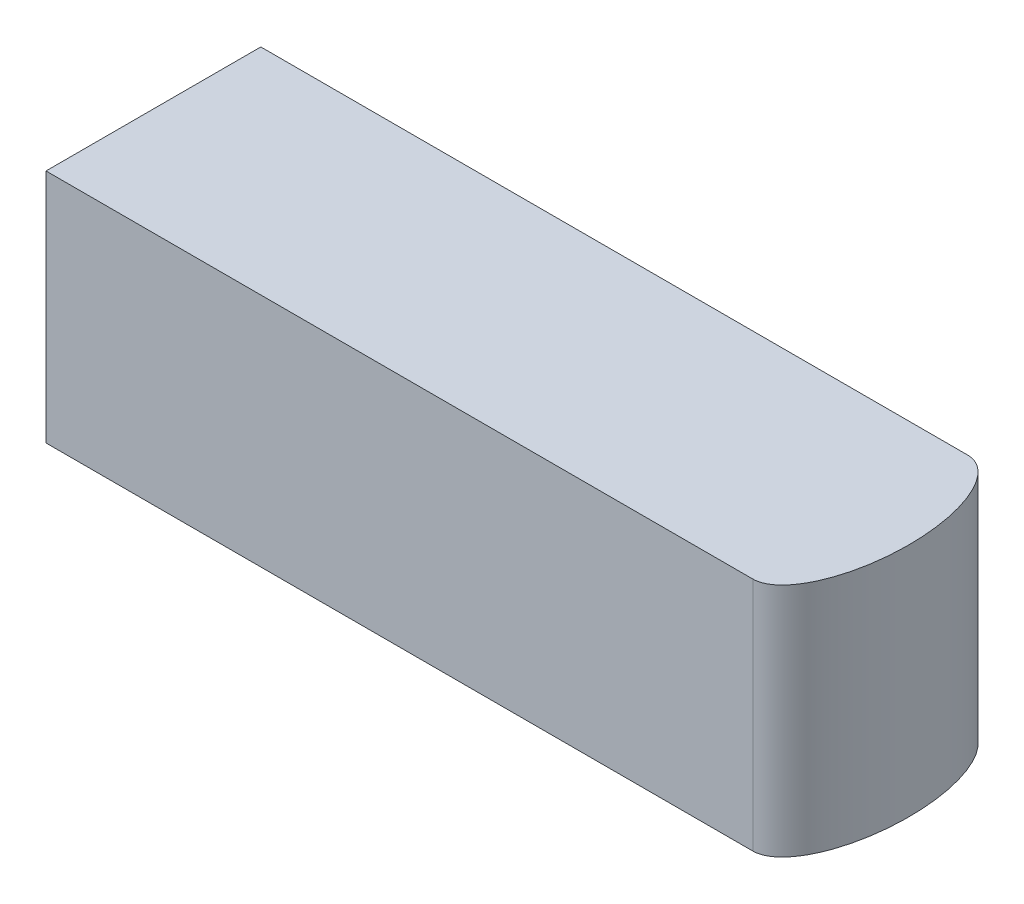
SolidWorks part; units mm, degrees
material "ABS"
ref_plane "Front Plane" through (0, 0, 0) normal (0, 0, 1) x (1, 0, 0)
ref_plane "Top Plane" through (0, 0, 0) normal (0, 1, 0) x (1, 0, 0)
ref_plane "Right Plane" through (0, 0, 0) normal (1, 0, 0) x (0, 0, -1)
sketch "Sketch1" plane through (0, 0, 0) normal (0, 1, 0) x (1, 0, 0)
  line L1 (-51, -15.5) -> (51, -15.5)
  line L2 (-51, -15.5) -> (-51, 15.5)
  line L3 (-51, 15.5) -> (51, 15.5)
  line L4 (51, -15.5) -> (51, 15.5) construction
  line L5 (-51, -15.5) -> (51, 15.5) construction
  line L6 (-51, 15.5) -> (51, -15.5) construction
  ellipse E1 centre (51, 0) end of major axis (51, -15.5) minor radius 7 (51, 15.5) -> (51, -15.5) cw
  point P0 (0, 0)
  dimension "D1" = 102
  dimension "D2" = 31
  dimension "D3" = 7
  dimension "D4" = 15.5
extrude "Boss-Extrude2" add sketch "Sketch1" along normal blind 34
sketch "Sketch2" plane through (0, 34, 0) normal (0, 1, 0) x (1, 0, 0)
  text T0 "Shitty Apex Legends Memes"
